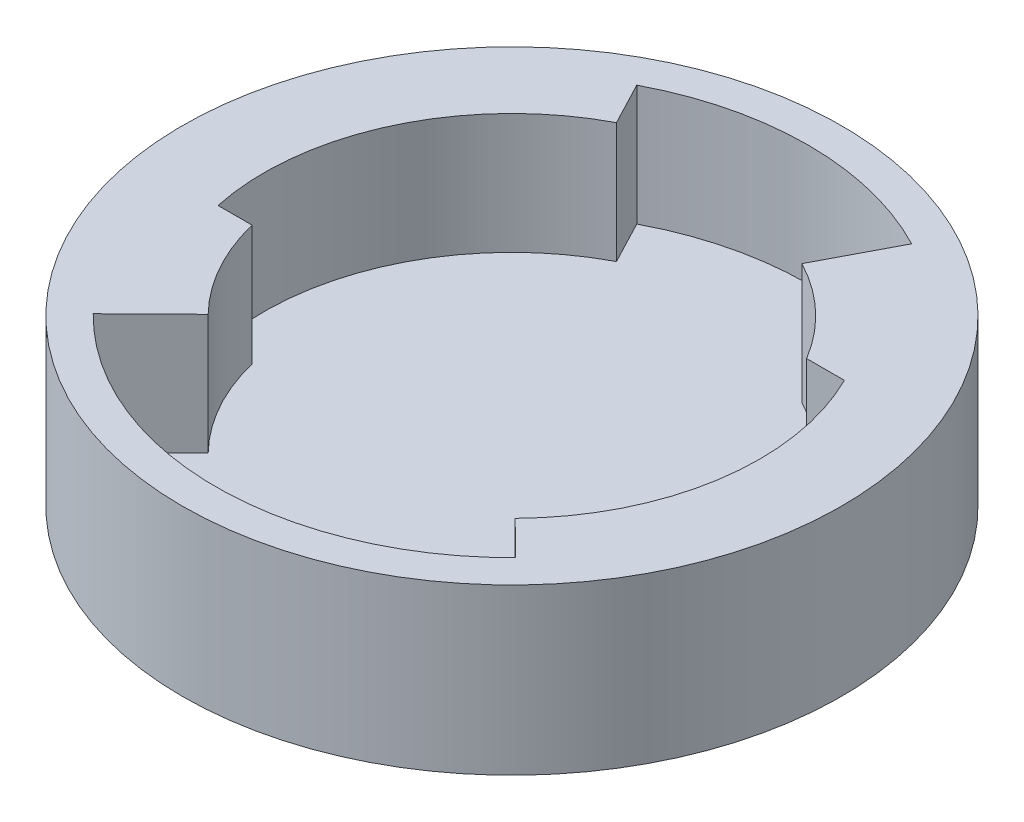
SolidWorks part; units mm, degrees
ref_plane "Front Plane" through (0, 0, 0) normal (0, 0, 1) x (1, 0, 0)
ref_plane "Top Plane" through (0, 0, 0) normal (0, 1, 0) x (1, 0, 0)
ref_plane "Right Plane" through (0, 0, 0) normal (1, 0, 0) x (0, 0, -1)
sketch "Sketch1" plane through (0, 0, 0) normal (0, 1, 0) x (1, 0, 0)
  circle A0 centre (0, 0) radius 50
  dimension "D1" = 100
extrude "Boss-Extrude1" add sketch "Sketch1" against normal blind 25
ref_plane "Plane1" through (0, 0, 0) normal (0, 1, 0) x (1, 0, 0)
sketch "Sketch2" plane through (0, 0, 0) normal (0, 1, 0) x (1, 0, 0)
  line L0 (0, -1000) -> (0, 1000) construction
  line L1 (-1000, 0) -> (1000, 0) construction
  line L2 (-20.85, 39.788) -> (-17.4616, 33.322)
  line L3 (20.85, 39.788) -> (15.1266, 28.866)
  line L4 (27.9544, 16.7513) -> (33.6847, 16.7513)
  line L5 (32.05, -31.4739) -> (26.8415, -26.359)
  line L6 (-32.05, -31.4739) -> (-23.2521, -22.8341)
  line L7 (-36.8054, -7.7864) -> (-31.6453, -7.7864)
  circle A0 centre (0, 0) radius 37.62 construction
  circle A1 centre (0, 0) radius 50 construction
  arc A2 (-20.85, 39.788) -> (20.85, 39.788) centre (0, 0) cw
  circle A3 centre (0, 0) radius 32.5892 construction
  arc A4 (21.4882, 24.5013) -> (27.9544, 16.7513) centre (0, 0) cw
  circle A5 centre (0, 0) radius 44.92 construction
  arc A6 (32.05, -31.4739) -> (-32.05, -31.4739) centre (0, 0) cw
  arc A7 (26.8415, -26.359) -> (33.6847, 16.7513) centre (0, 0) ccw
  arc A8 (-17.4616, 33.322) -> (-36.8054, -7.7864) centre (0, 0) ccw
  arc A9 (-23.2521, -22.8341) -> (-31.6453, -7.7864) centre (0, 0) cw
  arc A11 (15.1266, 28.866) -> (21.4882, 24.5013) centre (0, 0) cw
  point P11 (0, 44.92)
  point P20 (0, -44.92)
  dimension "D1" = 12.38
  dimension "D10" = 31.6453
  dimension "D11" = 91.039
  dimension "D8" = 33.6847
  dimension "D7" = 32.5892
  dimension "D2" = 41.7
  dimension "D3" = 7.3
  dimension "D4" = 15.3
  dimension "D5" = 7.75
  dimension "D6" = 64.1
extrude "Cut-Extrude1" cut sketch "Sketch2" against normal blind 18.25
